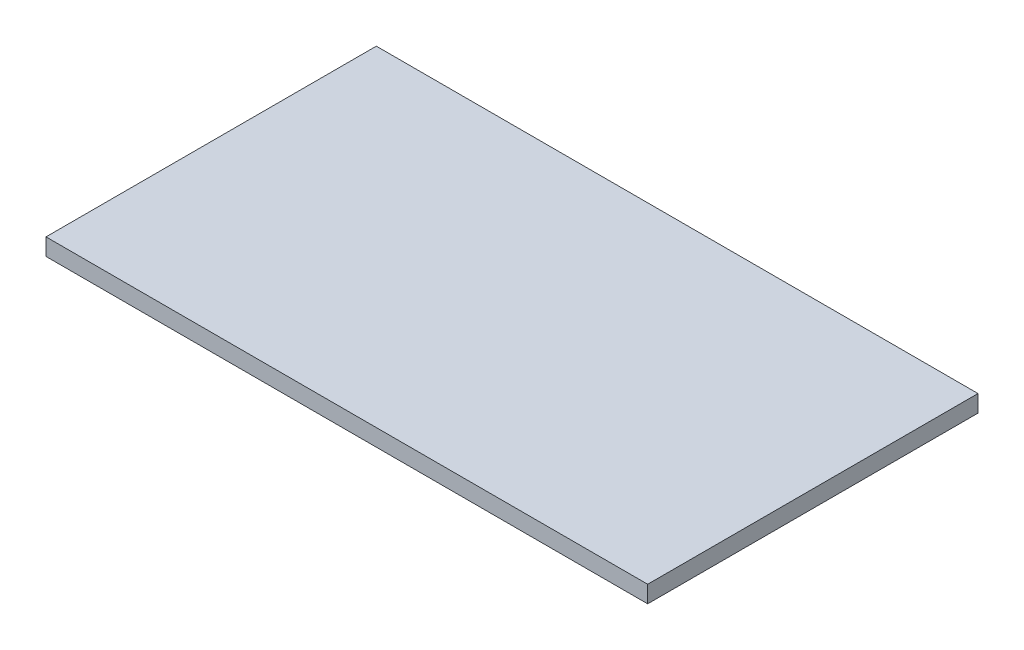
SolidWorks part; units mm, degrees
ref_plane "Front Plane" through (0, 0, 0) normal (0, 0, 1) x (1, 0, 0)
ref_plane "Top Plane" through (0, 0, 0) normal (0, 1, 0) x (1, 0, 0)
ref_plane "Right Plane" through (0, 0, 0) normal (1, 0, 0) x (0, 0, -1)
sketch "Sketch1" plane through (0, 0, 0) normal (0, 1, 0) x (1, 0, 0)
  line L1 (-80.9625, 44.45) -> (80.9625, 44.45)
  line L2 (-80.9625, 44.45) -> (-80.9625, -44.45)
  line L3 (-80.9625, -44.45) -> (80.9625, -44.45)
  line L4 (80.9625, 44.45) -> (80.9625, -44.45)
  line L5 (-80.9625, 44.45) -> (80.9625, -44.45) construction
  line L6 (-80.9625, -44.45) -> (80.9625, 44.45) construction
  point P0 (0, 0)
  dimension "D1" = 161.925
  dimension "D2" = 88.9
extrude "Boss-Extrude1" add sketch "Sketch1" along normal blind 4.572
